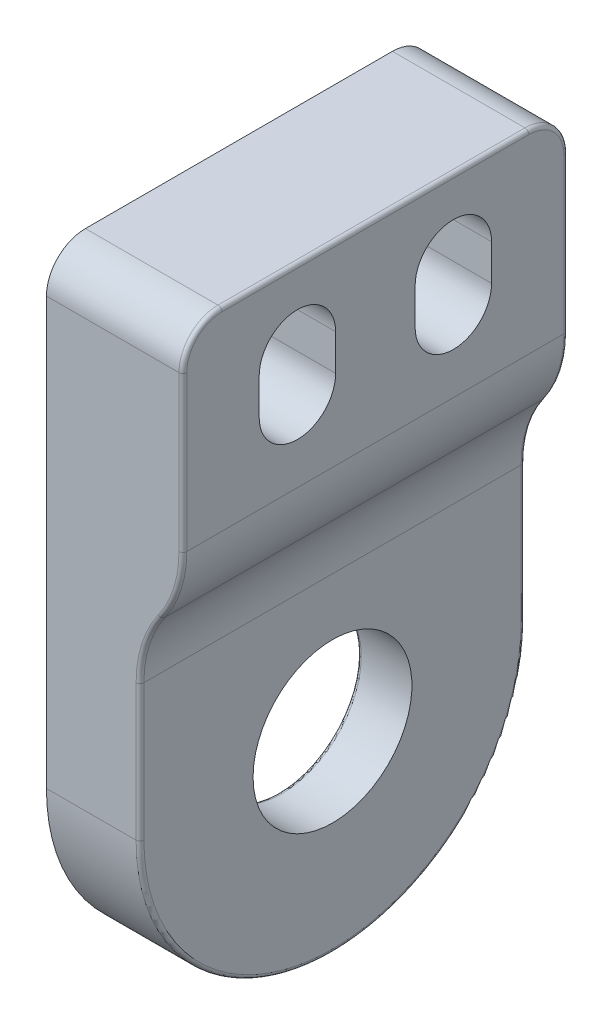
SolidWorks part; units mm, degrees
material "Delrin 2700 NC010, Low Viscosity Acetal Copolymer (SS)"
ref_plane "Front Plane" through (0, 0, 0) normal (0, 0, 1) x (1, 0, 0)
ref_plane "Top Plane" through (0, 0, 0) normal (0, 1, 0) x (1, 0, 0)
ref_plane "Right Plane" through (0, 0, 0) normal (1, 0, 0) x (0, 0, -1)
sketch "Sketch6" plane through (0, 0, 0) normal (1, 0, 0) x (0, 0, -1)
  line L0 (12.5413, 0) -> (12.5412, 30.3213)
  line L1 (12.5412, 30.3213) -> (-12.5413, 30.3212)
  line L4 (0, 12.5412) -> (0, -12.5412) construction
  line L7 (-12.5413, 30.3212) -> (-12.5412, 0)
  line L8 (-5.08, 25.2413) -> (-5.08, 22.8918) construction
  line L9 (-2.5908, 25.2413) -> (-2.5908, 22.8918)
  line L10 (-7.5692, 25.2413) -> (-7.5692, 22.8918)
  line L11 (5.08, 25.2413) -> (5.08, 22.8918) construction
  line L12 (7.5692, 25.2413) -> (7.5692, 22.8918)
  line L13 (2.5908, 25.2413) -> (2.5908, 22.8918)
  line L14 (-5.08, 24.0665) -> (5.08, 24.0665) construction
  line L15 (0, 24.0665) -> (0, 30.3213) construction
  line L16 (0, 17.8117) -> (0, 24.0665) construction
  circle A0 centre (0, 0) radius 5.1752
  arc A3 (-12.5412, 0) -> (12.5413, 0) centre (0, 0) ccw
  arc A5 (-2.5908, 25.2413) -> (-7.5692, 25.2413) centre (-5.08, 25.2413) ccw
  arc A6 (-7.5692, 22.8918) -> (-2.5908, 22.8918) centre (-5.08, 22.8918) ccw
  arc A7 (7.5692, 25.2413) -> (2.5908, 25.2413) centre (5.08, 25.2413) ccw
  arc A8 (2.5908, 22.8918) -> (7.5692, 22.8918) centre (5.08, 22.8918) ccw
  point P4 (-5.08, 24.0665)
  point P18 (5.08, 24.0665)
  dimension "D1" = 10.3505
  dimension "D3" = 25.0825
  dimension "D4" = 24.0665
  dimension "D2" = 5.08
  dimension "D5" = 2.3495
  dimension "D6" = 10.16
  dimension "D7" = 4.9784
extrude "Boss-Extrude1" add sketch "Sketch6" along normal blind 6.35
fillet "Fillet1" radius 2.54 2 edges at (3.175, 30.3213, -12.5412) (3.175, 30.3212, 12.5413)
sketch "Sketch11" plane through (0, 0, 0) normal (0, 0, 1) x (1, 0, 0)
  line L0 (3.556, -12.5413) -> (3.556, 8.89)
  line L1 (0, -12.5413) -> (6.35, -12.5413) construction
  line L2 (6.35, 27.7812) -> (6.35, 0) construction
  line L3 (6.35, 17.6852) -> (6.35, -12.5413)
  line L4 (6.35, -12.5413) -> (3.556, -12.5413)
  line L5 (0, 0) -> (0, -12.5413) construction
  arc A0 (3.556, 8.89) -> (4.953, 13.2876) centre (11.176, 8.89) cw
  arc A1 (4.953, 13.2876) -> (6.35, 17.6852) centre (-1.27, 17.6852) ccw
  dimension "D2" = 7.62
  dimension "D1" = 3.556
  dimension "D3" = 8.89
extrude "Cut-Extrude2" cut sketch "Sketch11" against normal through all both and the other way through all
sketch "Sketch18" plane through (0, 0, 0) normal (-1, 0, 0) x (0, 0, 1)
  line L0 (0, 0) -> (0, 41.405) construction
  line L1 (-3.81, 10.4389) -> (-3.81, 12.9789)
  line L2 (-3.81, 12.9789) -> (0, 12.9789)
  line L3 (0, 12.9789) -> (3.81, 12.9789)
  line L4 (3.81, 12.9789) -> (3.81, 10.4389)
  line L5 (-12.5413, 0) -> (-12.5412, 27.7812) construction
  line L6 (-10.0012, 30.3213) -> (10.0013, 30.3212) construction
  line L7 (12.5413, 27.7812) -> (12.5413, 0) construction
  line L8 (-12.5413, 0) -> (-12.5412, 27.7812)
  line L9 (-10.0012, 30.3213) -> (10.0013, 30.3212)
  line L10 (12.5413, 27.7812) -> (12.5413, 0)
  circle A0 centre (0, 0) radius 11.1125
  arc A1 (-12.5413, 0) -> (12.5413, 0) centre (0, 0) ccw construction
  arc A4 (-12.5413, 0) -> (12.5413, 0) centre (0, 0) ccw
  dimension "D1" = 22.225
  dimension "D2" = 7.62
  dimension "D3" = 2.54
extrude "Boss-Extrude6" add sketch "Sketch18" along normal blind 2.54
fillet "Fillet2" radius 0.254 17 edges at (-2.54, 11.7089, 3.81) (-2.54, 12.9789, 0) (-2.54, 11.7089, -3.81) (0, 0, -5.1752) (-2.54, -11.1125, 0) (-1.27, 10.4389, 3.81) (-1.27, 12.9789, 3.81) (-1.27, 12.9789, -3.81) (-1.27, 10.4389, -3.81) (-2.54, 24.0665, 2.5908) (-2.54, 24.0665, 7.5692) (-2.54, 27.7305, 5.08) (-2.54, 20.4026, 5.08) (-2.54, 24.0665, -7.5692) (-2.54, 24.0665, -2.5908) (-2.54, 27.7305, -5.08) (-2.54, 20.4026, -5.08)
fillet "Fillet3" radius 0.254 12 edges at (3.556, 4.445, -12.5413) (3.9136, 11.1971, -12.5413) (5.9924, 15.3781, -12.5413) (6.35, 22.7332, -12.5413) (6.35, 29.5773, -11.7973) (6.35, 30.3213, 0) (6.35, 29.5773, 11.7973) (6.35, 22.7332, 12.5413) (5.9924, 15.3781, 12.5413) (3.9136, 11.1971, 12.5413) (3.556, 4.445, 12.5413) (3.556, -12.5413, 0)
